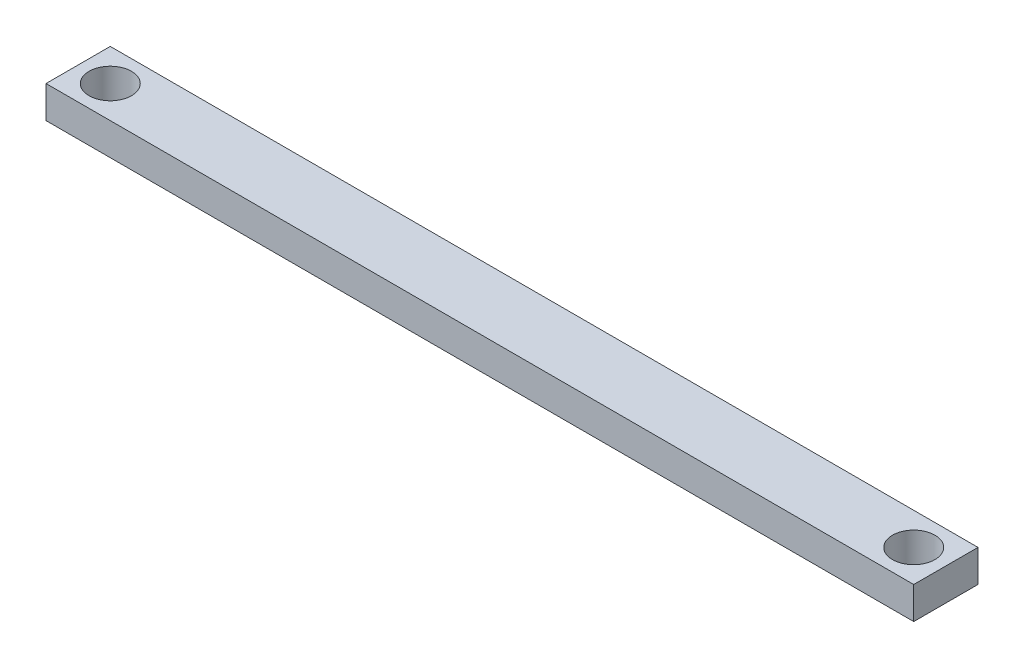
SolidWorks part; units mm, degrees
ref_plane "前视基准面" through (0, 0, 0) normal (0, 0, 1) x (1, 0, 0)
ref_plane "上视基准面" through (0, 0, 0) normal (0, 1, 0) x (1, 0, 0)
ref_plane "右视基准面" through (0, 0, 0) normal (1, 0, 0) x (0, 0, -1)
other "Configuration Table"
sketch "草图1" plane through (0, 0, 0) normal (0, 1, 0) x (1, 0, 0)
  line L1 (0, 0) -> (675, 0)
  line L2 (0, 0) -> (0, 50)
  line L3 (0, 50) -> (675, 50)
  line L4 (675, 0) -> (675, 50)
  circle A0 centre (25, 25) radius 16.5
  circle A1 centre (650, 25) radius 16.5
  point P11 (706.7877, 23.0262)
  point P12 (604.4913, 50)
  dimension "D3" = 33
  dimension "D6" = 33
  dimension "D1" = 50
  dimension "D2" = 675
  dimension "D4" = 25
  dimension "D5" = 25
  dimension "D7" = 25
  dimension "D8" = 25
extrude "凸台-拉伸1" add sketch "草图1" along normal blind 25
